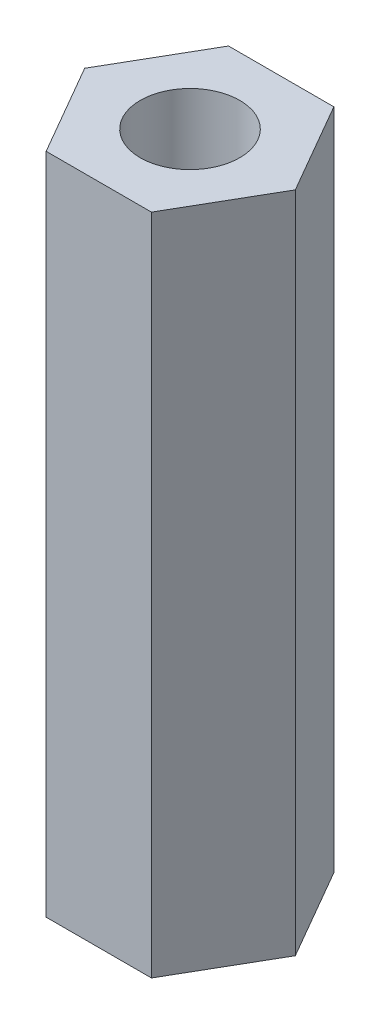
SolidWorks part; units mm, degrees
ref_plane "前视基准面" through (0, 0, 0) normal (0, 0, 1) x (1, 0, 0)
ref_plane "上视基准面" through (0, 0, 0) normal (0, 1, 0) x (1, 0, 0)
ref_plane "右视基准面" through (0, 0, 0) normal (1, 0, 0) x (0, 0, -1)
sketch "草图1" plane through (0, 0, 0) normal (0, 1, 0) x (1, 0, 0)
  line L1 (-4.1472, 7.5722) -> (-5.7349, 10.3222)
  line L2 (-5.7349, 10.3222) -> (-8.9103, 10.3222)
  line L3 (-8.9103, 10.3222) -> (-10.498, 7.5722)
  line L4 (-10.498, 7.5722) -> (-8.9103, 4.8222)
  line L5 (-8.9103, 4.8222) -> (-5.7349, 4.8222)
  line L6 (-5.7349, 4.8222) -> (-4.1472, 7.5722)
  circle A0 centre (-7.3226, 7.5722) radius 1.5
  circle A1 centre (-7.3226, 7.5722) radius 2.75 construction
extrude "凸台-拉伸1" add sketch "草图1" along normal blind 20
